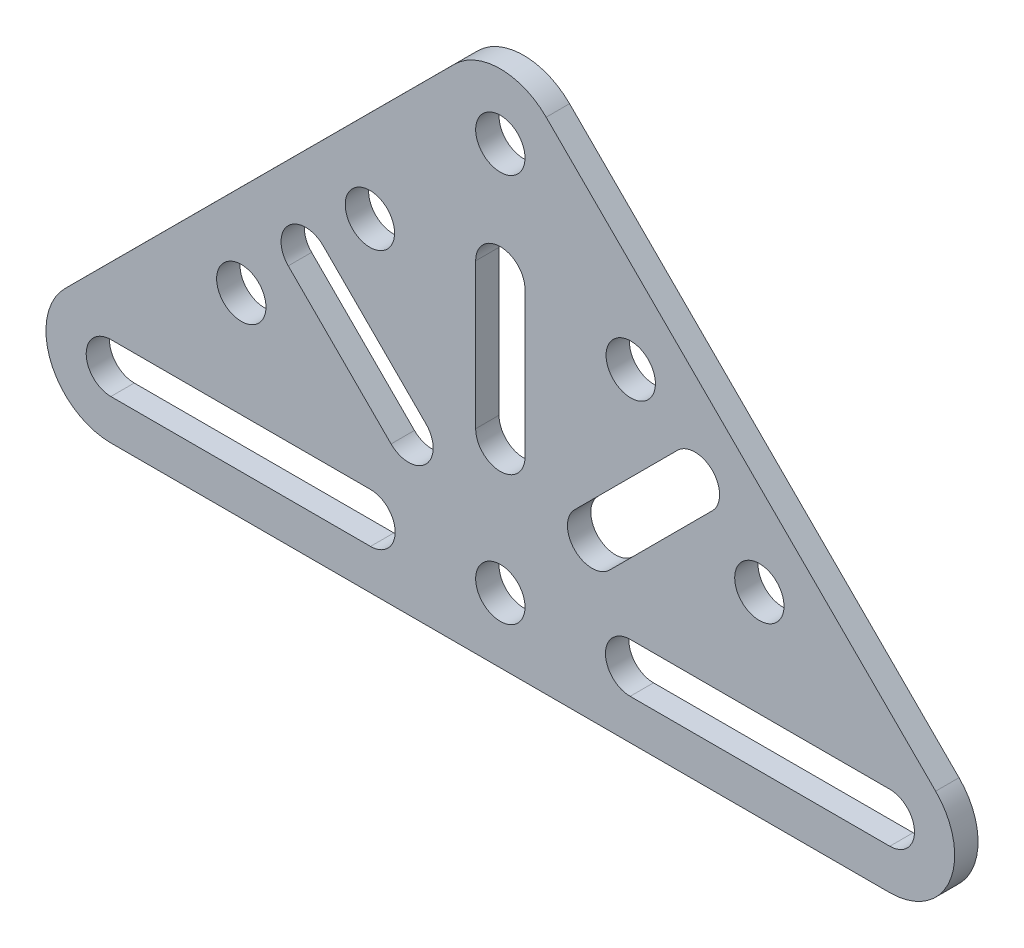
SolidWorks part; units mm, degrees
ref_plane "Front Plane" through (0, 0, 0) normal (0, 0, 1) x (1, 0, 0)
ref_plane "Top Plane" through (0, 0, 0) normal (0, 1, 0) x (1, 0, 0)
ref_plane "Right Plane" through (0, 0, 0) normal (1, 0, 0) x (0, 0, -1)
sketch "Sketch1" plane through (0, 0, 0) normal (0, 0, 1) x (1, 0, 0)
  line L0 (0, 0) -> (0, 38.0526) construction
  line L1 (-38.1, 0) -> (38.1, 0) construction
  line L2 (38.1, 0) -> (0, 38.0526) construction
  line L3 (-38.1, 0) -> (0, 38.0526) construction
  line L4 (0, 0) -> (19.0381, 19.0381) construction
  line L5 (0, 0) -> (-19.0381, 19.0381) construction
  line L6 (-42.5873, 4.4929) -> (-4.4873, 42.5455)
  line L7 (42.5873, 4.4929) -> (4.4873, 42.5455)
  line L8 (-38.1, -6.35) -> (38.1, -6.35)
  line L9 (-53.4438, -6.35) -> (0, 47.0272) construction
  line L10 (-53.4438, -6.35) -> (53.4438, -6.35) construction
  line L11 (53.4438, -6.35) -> (0, 47.0272) construction
  arc A0 (-42.5873, 4.4929) -> (-38.1, -6.35) centre (-38.1, 0) ccw
  arc A1 (-4.4873, 42.5455) -> (4.4873, 42.5455) centre (0, 38.0526) cw
  arc A2 (42.5873, 4.4929) -> (38.1, -6.35) centre (38.1, 0) cw
  dimension "D5" = 6.35
  dimension "D1" = 45
  dimension "D2" = 76.2
  dimension "D3" = 53.848
  dimension "D4" = 6.35
extrude "Boss-Extrude1" add sketch "Sketch1" along normal blind 2.286
sketch "Sketch2" plane through (0, 0, 2.286) normal (0, 0, 1) x (1, 0, 0)
  line L0 (0, 0) -> (0, 38.0526) construction
  line L1 (-38.1, 0) -> (0, 38.0526) construction
  circle A0 centre (0, 0) radius 2.413
  circle A1 centre (0, 38.0526) radius 2.413
  circle A2 centre (-25.3401, 12.744) radius 2.413
  circle A3 centre (25.3401, 12.744) radius 2.413
  circle A4 centre (-12.7599, 25.3085) radius 2.413
  circle A5 centre (12.7599, 25.3085) radius 2.413
  dimension "D1" = 4.826
  dimension "D2" = 18.034
  dimension "D3" = 35.814
extrude "Cut-Extrude1" cut sketch "Sketch2" against normal through all
sketch "Sketch3" plane through (0, 0, 2.286) normal (0, 0, 1) x (1, 0, 0)
  line L1 (-38.1, 2.413) -> (-12.7, 2.413)
  line L3 (-38.1, -2.413) -> (-12.7, -2.413)
  arc A0 (-38.1, 2.413) -> (-38.1, -2.413) centre (-38.1, 0) ccw
  arc A1 (-12.7, 2.413) -> (-12.7, -2.413) centre (-12.7, 0) cw
  circle A2 centre (0, 0) radius 2.413 construction
  dimension "D1" = 25.4
extrude "Cut-Extrude2" cut sketch "Sketch3" against normal through all
mirror "Mirror1" about plane through (0, 0, 0) normal (1, 0, 0) of "Cut-Extrude2"
sketch "Sketch4" plane through (0, 0, 2.286) normal (0, 0, 1) x (1, 0, 0)
  line L0 (-20.7454, 17.3329) -> (-10.6876, 7.2751)
  line L1 (0, 0) -> (-19.0381, 19.0381) construction
  line L3 (-17.3329, 20.7454) -> (-7.2751, 10.6876)
  line L4 (-38.1, 0) -> (0, 38.0526) construction
  arc A0 (-17.3329, 20.7454) -> (-20.7454, 17.3329) centre (-19.0392, 19.0392) ccw
  arc A1 (-7.2751, 10.6876) -> (-10.6876, 7.2751) centre (-8.9813, 8.9813) cw
  circle A2 centre (-25.3401, 12.744) radius 2.413 construction
  dimension "D1" = 14.224
extrude "Cut-Extrude3" cut sketch "Sketch4" against normal through all
pattern_circular "CirPattern1" count 3 over 90 about axis through (0, 0, 0) along (0, 0, 1) of "Cut-Extrude3"
